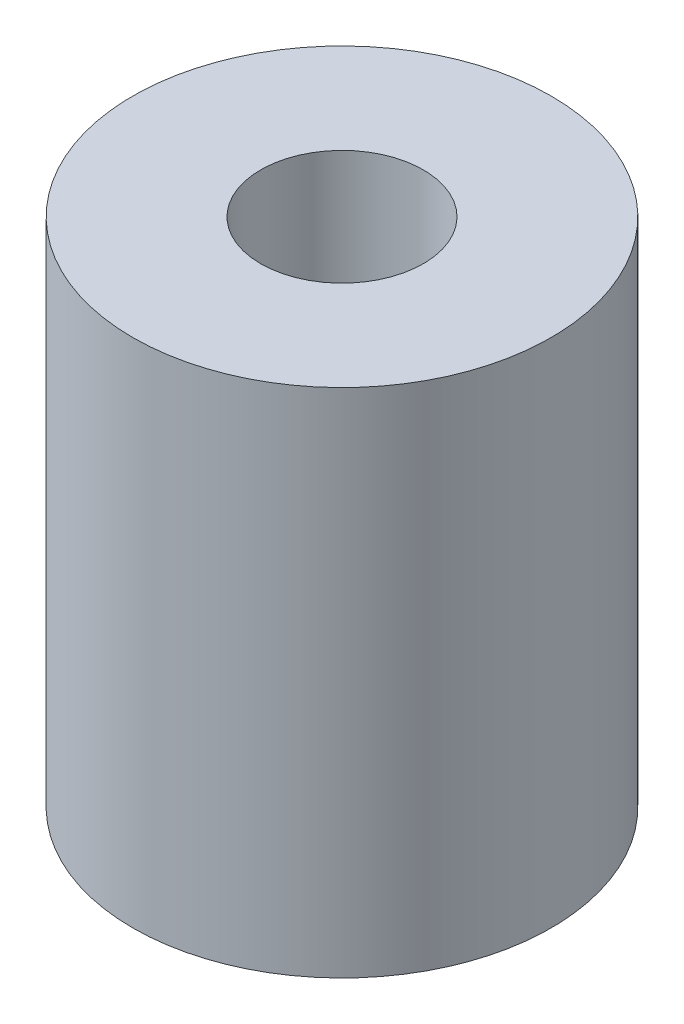
SolidWorks part; units mm, degrees
material "PETG"
ref_plane "Front Plane" through (0, 0, 0) normal (0, 0, 1) x (1, 0, 0)
ref_plane "Top Plane" through (0, 0, 0) normal (0, 1, 0) x (1, 0, 0)
ref_plane "Right Plane" through (0, 0, 0) normal (1, 0, 0) x (0, 0, -1)
sketch "Sketch1" plane through (0, 0, 0) normal (0, 1, 0) x (1, 0, 0)
  circle A0 centre (0, 0) radius 4.5
  circle A1 centre (0, 0) radius 1.75
  dimension "D1" = 3.5
  dimension "D2" = 9
extrude "Boss-Extrude1" add sketch "Sketch1" along normal blind 11
